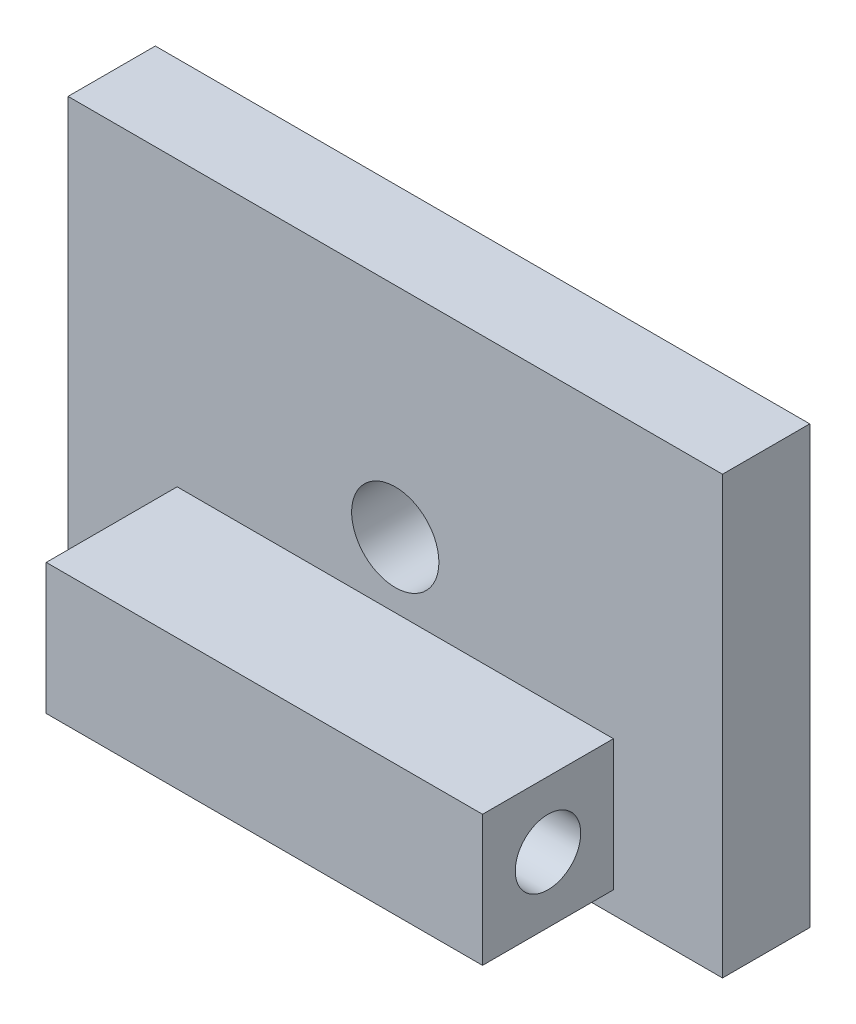
SolidWorks part; units mm, degrees
ref_plane "Front Plane" through (0, 0, 0) normal (0, 0, 1) x (1, 0, 0)
ref_plane "Top Plane" through (0, 0, 0) normal (0, 1, 0) x (1, 0, 0)
ref_plane "Right Plane" through (0, 0, 0) normal (1, 0, 0) x (0, 0, -1)
sketch "Sketch1" plane through (0, 0, 0) normal (0, 0, 1) x (1, 0, 0)
  line L1 (-15, 10) -> (15, 10)
  line L2 (-15, 10) -> (-15, -10)
  line L3 (-15, -10) -> (15, -10)
  line L4 (15, 10) -> (15, -10)
  line L5 (-15, 10) -> (15, -10) construction
  line L6 (-15, -10) -> (15, 10) construction
  circle A0 centre (0, 0) radius 2
  point P0 (0, 0)
  dimension "D3" = 4
  dimension "D1" = 20
  dimension "D2" = 30
extrude "Boss-Extrude1" add sketch "Sketch1" along normal blind 4
sketch "Sketch2" plane through (0, 0, 4) normal (0, 0, 1) x (1, 0, 0)
  line L0 (0, -2) -> (0, -10) construction
  line L1 (-10, -3) -> (10, -3)
  line L2 (-10, -3) -> (-10, -9)
  line L3 (-10, -9) -> (10, -9)
  line L4 (10, -3) -> (10, -9)
  line L5 (-10, -3) -> (10, -9) construction
  line L6 (-10, -9) -> (10, -3) construction
  line L7 (-15, -10) -> (15, -10) construction
  circle A0 centre (0, 0) radius 2 construction
  point P0 (0, -6)
  point P5 (-2.2221, -1.5022)
  point P6 (0, 0)
  point P8 (0, 0)
  point P11 (0, -6)
  point P14 (0, 0)
  point P15 (0, -2)
  point P18 (-1.3601, -1.4663)
  dimension "D1" = 6
  dimension "D2" = 20
extrude "Boss-Extrude2" add sketch "Sketch2" along normal blind 6 contours L2 L1 L4 L3
sketch "Sketch4" plane through (10, 0, 0) normal (1, 0, 0) x (0, 0, -1)
  line L0 (-10, -3) -> (-4, -3) construction
  line L1 (-10, -3) -> (-10, -9) construction
  circle A0 centre (-7, -6) radius 1.5
  point P2 (0, 0)
  point P5 (-7, -3)
  point P8 (-10, -6)
  dimension "D1" = 3
extrude "Cut-Extrude1" cut sketch "Sketch4" against normal blind 18
sketch "Sketch5" plane through (-8, 0, 0) normal (1, 0, 0) x (0, 0, -1)
  circle A0 centre (-7, -6) radius 1.2
  dimension "D1" = 2.4
extrude "Cut-Extrude2" cut sketch "Sketch5" against normal blind 6
